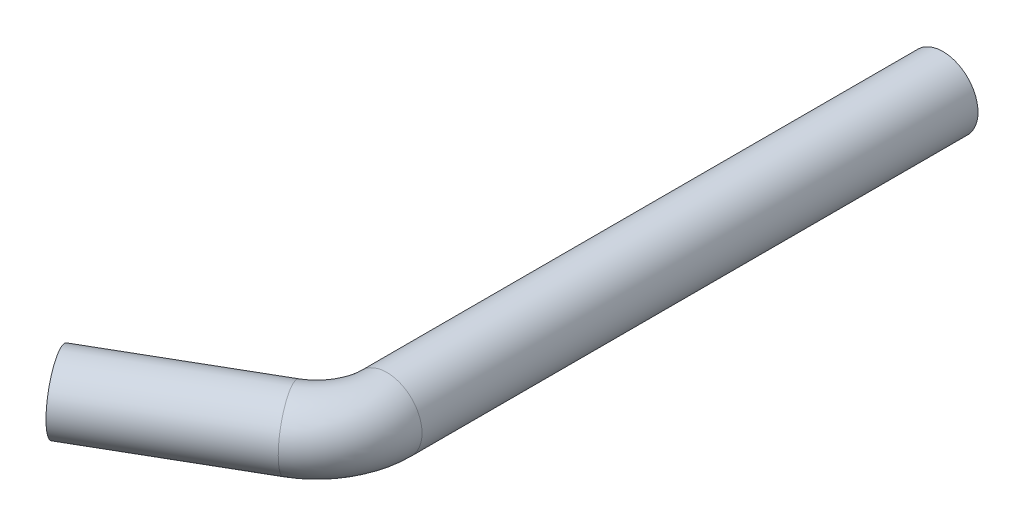
SolidWorks part; units mm, degrees
material "1023 Carbon Steel Sheet (SS)"
ref_plane "Front Plane" through (0, 0, 0) normal (0, 0, 1) x (1, 0, 0)
ref_plane "Top Plane" through (0, 0, 0) normal (0, 1, 0) x (1, 0, 0)
ref_plane "Right Plane" through (0, 0, 0) normal (1, 0, 0) x (0, 0, -1)
sketch "Sketch1" plane through (0, 0, 0) normal (0, 0, 1) x (1, 0, 0)
  circle A0 centre (0, 0) radius 5
  dimension "D1" = 10
sketch "Sketch4" plane through (0, 0, 0) normal (0, 1, 0) x (1, 0, 0)
  line L0 (0, 0) -> (0, -79.2265)
  line L1 (-5, -87.8868) -> (-25.9808, -100)
  line L2 (0, 55.1644) -> (0, -153.885) construction
  arc A0 (0, -79.2265) -> (-5, -87.8868) centre (-10, -79.2265) cw
  point P6 (0, -85)
  point P9 (0, -85)
  point P10 (0, -85)
  dimension "D4" = 10
  dimension "D1" = 85
  dimension "D2" = 15
  dimension "D3" = 60
sweep "Sweep1" add profiles "Sketch1" path "Sketch4"
